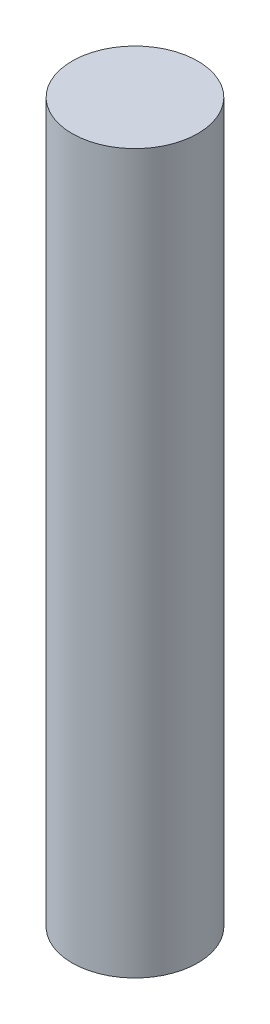
SolidWorks part; units mm, degrees
ref_plane "Front Plane" through (0, 0, 0) normal (0, 0, 1) x (1, 0, 0)
ref_plane "Top Plane" through (0, 0, 0) normal (0, 1, 0) x (1, 0, 0)
ref_plane "Right Plane" through (0, 0, 0) normal (1, 0, 0) x (0, 0, -1)
sketch "Sketch1" plane through (0, 0, 0) normal (0, 1, 0) x (1, 0, 0)
  circle A0 centre (0, 0) radius 3.5
  dimension "D1" = 7
extrude "Boss-Extrude1" add sketch "Sketch1" along normal blind 40 contours A0
